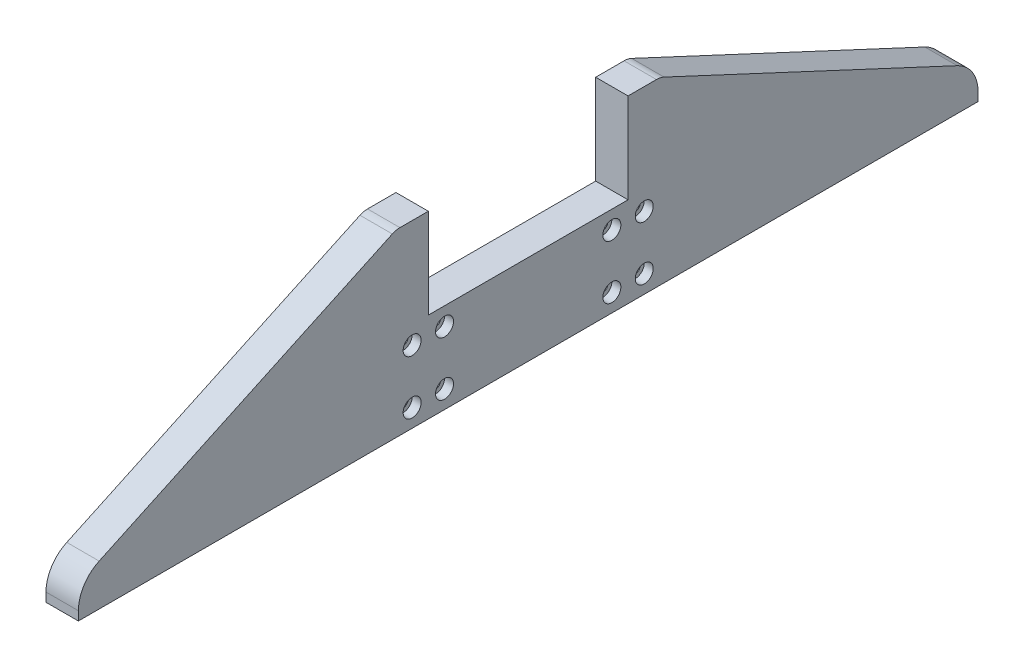
SolidWorks part; units mm, degrees
material "Beech"
ref_plane "Front Plane" through (0, 0, 0) normal (0, 0, 1) x (1, 0, 0)
ref_plane "Top Plane" through (0, 0, 0) normal (0, 1, 0) x (1, 0, 0)
ref_plane "Right Plane" through (0, 0, 0) normal (1, 0, 0) x (0, 0, -1)
sketch "Sketch1" plane through (0, 0, 0) normal (0, 0, 1) x (1, 0, 0)
  line L1 (0, 0) -> (18, 0)
  line L2 (0, 0) -> (0, 100)
  line L3 (0, 100) -> (18, 100)
  line L4 (18, 0) -> (18, 100)
  dimension "D1" = 100
  dimension "D2" = 18
extrude "base" add sketch "Sketch1" along normal blind 500
sketch "Sketch2" plane through (0, 0, 0) normal (-1, 0, 0) x (0, 0, 1)
  line L0 (250, 50) -> (250, 0) construction
  line L1 (194.5, 100) -> (305.5, 100)
  line L2 (194.5, 100) -> (194.5, 50)
  line L3 (194.5, 50) -> (305.5, 50)
  line L4 (305.5, 100) -> (305.5, 50)
  line L5 (500, 100) -> (0, 100) construction
  line L6 (500, 0) -> (0, 0) construction
  dimension "D1" = 50
  dimension "D2" = 111
extrude "lap joint cutout" cut sketch "Sketch2" against normal through all
hole_wizard "lap joint bolt hole pattern" positions "Sketch3" profile "Sketch4" counterbore size "M5" standard "ANSI Metric" end condition through all
sketch "Sketch3" plane through (18, 0, 0) normal (1, 0, 0) x (0, 0, -1)
  line L1 (-296.5, 40) -> (-203.5, 40)
  line L2 (-296.5, 40) -> (-296.5, 10)
  line L3 (-296.5, 10) -> (-203.5, 10)
  line L4 (-203.5, 40) -> (-203.5, 10)
  line L5 (-250, 40) -> (-250, 50)
  line L6 (-194.5, 50) -> (-305.5, 50) construction
  line L8 (-250, 10) -> (-250, 0)
  line L9 (-500, 0) -> (0, 0) construction
  point P1 (-296.5, 40)
  point P2 (-203.5, 10)
  point P63 (-296.5, 10)
  point P64 (-203.5, 40)
  dimension "D1" = 93
  dimension "D2" = 30
sketch "Sketch4" plane through (18, 40, 296.5) normal (0, 1, 0) x (0, 0, -1)
  line L0 (0, 0) -> (0, 18)
  line L1 (0, 18) -> (2.75, 18)
  line L3 (2.75, 18) -> (2.75, 5)
  line L4 (2.75, 5) -> (5, 5)
  line L5 (5, 5) -> (5, 0)
  line L7 (5, 0) -> (0, 0)
  line L11 (0, -6.35) -> (0, 107.95) construction
  dimension "Thru Hole Dia." = 5.5
  dimension "Thru Hole Depth" = 18
  dimension "C'Bore Dia." = 10
  dimension "C'Bore Depth" = 5
chamfer "chamfer front" distance 176.5 angle 25 1 edges at (9, 100, 0)
chamfer "chamfer rear" distance 176.5 angle 25 1 edges at (9, 100, 500)
fillet "break chamfer outer corners" radius 20 2 edges at (9, 17.6967, 0) (9, 17.6967, 500)
hole_wizard "cross tie bolt hole pattern" positions "Sketch7" profile "Sketch6" counterbore size "M5" standard "ANSI Metric" end condition through all
sketch "Sketch7" plane through (18, 0, 0) normal (1, 0, 0) x (0, 0, -1)
  line L1 (-323.5, 50) -> (-305.5, 50)
  line L2 (-323.5, 50) -> (-323.5, 0)
  line L3 (-323.5, 0) -> (-305.5, 0)
  line L4 (-305.5, 50) -> (-305.5, 0)
  line L5 (-500, 0) -> (0, 0) construction
  line L6 (-305.5, 50) -> (-305.5, 100) construction
  line L8 (-194.5, 50) -> (-305.5, 50) construction
  line L10 (-314.5, 50) -> (-314.5, 0)
  line L12 (-314.5, 40) -> (-323.5, 25)
  line L13 (-323.5, 25) -> (-314.5, 10)
  point P88 (-314.5, 40)
  point P90 (-314.5, 10)
  dimension "D2" = 30
  dimension "D1" = 18
sketch "Sketch6" plane through (18, 40, 314.5) normal (0, 1, 0) x (0, 0, -1)
  line L0 (0, 0) -> (0, 18)
  line L1 (0, 18) -> (2.75, 18)
  line L3 (2.75, 18) -> (2.75, 5)
  line L4 (2.75, 5) -> (5, 5)
  line L5 (5, 5) -> (5, 0)
  line L7 (5, 0) -> (0, 0)
  line L11 (0, -6.35) -> (0, 107.95) construction
  dimension "Thru Hole Dia." = 5.5
  dimension "Thru Hole Depth" = 18
  dimension "C'Bore Dia." = 10
  dimension "C'Bore Depth" = 5
ref_plane "midplane in length dimension" through (0, 0, 250) normal (0, 0, -1) x (-1, 0, 0)
mirror "mirror cross tie bolt hole pattern" about plane through (0, 0, 250) normal (0, 0, -1) of "cross tie bolt hole pattern"
fillet "Fillet1" radius 10 2 edges at (9, 100, 323.5) (9, 100, 176.5)
equation "\"board_thickness\" = 18mm"
equation "\"way_width\"= 75mm"
equation "\"way_thickness\"= 50mm"
equation "\"radial_clearance\"= 0.1mm"
equation "\"slider_width\"= \"way_width\"-2* \"radial_clearance\""
equation "\"slider_thickness\" = \"way_thickness\" - 2 * \"radial_clearance\""
equation "\"column_width\"= \"way_width\" + 2 * \"board_thickness\""
equation "\"boxway_slot_width\" = 50mm"
equation "\"keeper_rail_width\" = (\"column_width\" - \"boxway_slot_width\")/2"
equation "\"slider_length\" = 125mm"
equation "\"nut_diameter\"= 22mm"
equation "\"nut_length\"= 15mm"
equation "\"leadscrew_diameter\"= 10mm"
equation "\"leadscrew_radial_clearance\"= 1mm"
equation "\"bearing_bolt_pattern_width\" = 35mm"
equation "\"bearing_bolt_pattern_height\" = 60mm"
equation "\"desktop_bolt_pattern_width\" = 30mm"
equation "\"desktop_bolt_pattern_height\" = 30mm"
equation "\"bearing_bolt_nut_counterbore_diameter\" = 12mm"
equation "\"bearing_bolt_nut_counterbore_depth\"= 10mm"
equation "\"desktop_depth\"= 500mm"
equation "\"desktop_width\"= 650mm"
equation "\"desktop_thickness\"= 18mm"
equation "\"leg_height\"=100mm"
equation "\"D1@Sketch1\"=\"leg_height\""
equation "\"leg_width\"=18mm"
equation "\"D2@Sketch1\"=\"leg_width\""
equation "\"leg_length\"=500mm"
equation "\"D1@base\" = \"leg_length\""
equation "\"lap_joint_height\" = 50mm"
equation "\"D1@Sketch2\"=\"lap_joint_height\""
equation "\"D2@Sketch2\"=\"column_width\""
equation "\"lap_dowel_diameter\"= 8mm"
equation "\"D1@Sketch3\"=\"column_width\"-\"board_thickness\""
equation "\"lap_dowel_hole_z_spacing\"=30"
equation "\"D2@Sketch3\"=\"lap_dowel_hole_z_spacing\""
equation "\"D1@Sketch7\"=\"board_thickness\""
equation "\"D2@Sketch7\"=\"lap_dowel_hole_z_spacing\""
equation "\"D1@chamfer front\"=((\"leg_length\"-\"column_width\")/2) - \"board_thickness\""
equation "\"D1@chamfer rear\"=((\"leg_length\"-\"column_width\")/2) - \"board_thickness\""
